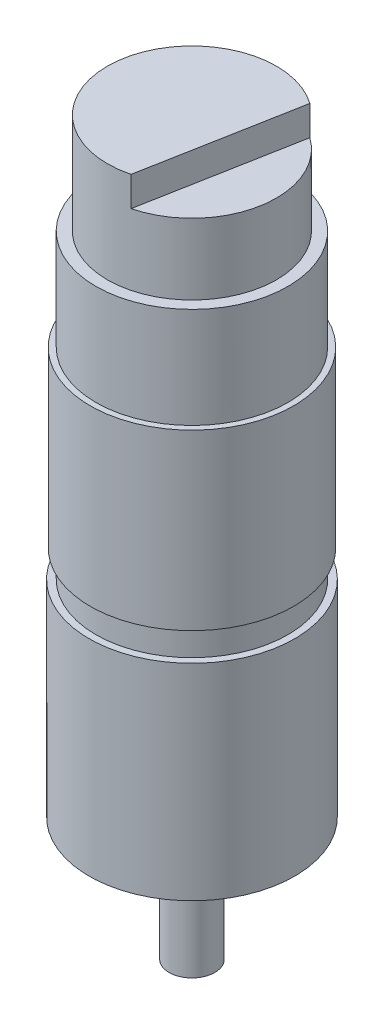
SolidWorks part; units mm, degrees
ref_plane "Front Plane" through (0, 0, 0) normal (0, 0, 1) x (1, 0, 0)
ref_plane "Top Plane" through (0, 0, 0) normal (0, 1, 0) x (1, 0, 0)
ref_plane "Right Plane" through (0, 0, 0) normal (1, 0, 0) x (0, 0, -1)
sketch "Sketch5" plane through (0, 0, 0) normal (0, 1, 0) x (1, 0, 0)
  circle A0 centre (0, 0) radius 22.5
extrude "Boss-Extrude4" add sketch "Sketch5" along normal blind 45
sketch "Sketch6" plane through (0, 45, 0) normal (0, 1, 0) x (-1, 0, 0)
  circle A0 centre (0, 0) radius 21
extrude "Boss-Extrude5" add sketch "Sketch6" along normal blind 6
sketch "Sketch7" plane through (0, 51, 0) normal (0, 1, 0) x (-1, 0, 0)
  circle A0 centre (0, 0) radius 22.25
extrude "Boss-Extrude6" add sketch "Sketch7" along normal blind 38
sketch "Sketch8" plane through (0, 89, 0) normal (0, 1, 0) x (-1, 0, 0)
  circle A0 centre (0, 0) radius 21
extrude "Boss-Extrude7" add sketch "Sketch8" along normal blind 22
sketch "Sketch9" plane through (0, 111, 0) normal (0, 1, 0) x (-1, 0, 0)
  circle A0 centre (0, 0) radius 18.5
extrude "Boss-Extrude9" add sketch "Sketch9" along normal blind 22
sketch "Sketch10" plane through (0, 133, 0) normal (0, 1, 0) x (-1, 0, 0)
  line L0 (-10.7161, -15.0803) -> (-4.5973, 17.9197)
  circle A0 centre (0, 0) radius 18.5 construction
  arc A1 (-4.5973, 17.9197) -> (-10.7161, -15.0803) centre (0, 0) ccw
extrude "Cut-Extrude1" cut sketch "Sketch10" against normal blind 6.5
sketch "Sketch16" plane through (0, 89, 0) normal (0, 1, 0) x (1, 0, 0)
  line L0 (0.6512, 20.9899) -> (0.69, 22.2393)
  line L1 (6.6895, 19.906) -> (7.0877, 21.0909)
  circle A0 centre (0, 0) radius 22.25 construction
  arc A1 (7.0877, 21.0909) -> (0.69, 22.2393) centre (0, 0) ccw
  arc A2 (6.6895, 19.906) -> (0.6512, 20.9899) centre (0, 0) ccw
  dimension "D1" = 6.5
extrude "Cut-Extrude3" cut sketch "Sketch16" against normal blind 38
sketch "Sketch17" plane through (0, 0, 0) normal (0, -1, 0) x (1, 0, 0)
  line L1 (-17.5646, -12) -> (17.5646, -12)
  line L2 (-17.5646, -12) -> (-17.5646, 12)
  line L3 (-17.5646, 12) -> (17.5646, 12)
  line L4 (17.5646, -12) -> (17.5646, 12)
  line L5 (-17.5646, -12) -> (17.5646, 12) construction
  line L6 (-17.5646, 12) -> (17.5646, -12) construction
  circle A0 centre (0, 0) radius 13
extrude "Boss-Extrude11" add sketch "Sketch17" along normal blind 2 contours L1 A0 L3
sketch "Sketch19" plane through (0, -2, 0) normal (0, -1, 0) x (1, 0, 0)
  circle A0 centre (0, 0) radius 5
extrude "Boss-Extrude12" add sketch "Sketch19" along normal blind 25
sketch "Sketch20" plane through (0, 0, 0) normal (0, -1, 0) x (1, 0, 0)
  line L1 (-12.578, -12.1673) -> (12.578, -12.1673)
  line L2 (-12.578, -12.1673) -> (-12.578, 12.1673)
  line L3 (-12.578, 12.1673) -> (12.578, 12.1673)
  line L4 (12.578, -12.1673) -> (12.578, 12.1673)
  line L5 (-12.578, -12.1673) -> (12.578, 12.1673) construction
  line L6 (-12.578, 12.1673) -> (12.578, -12.1673) construction
  circle A0 centre (0, 0) radius 17.5 construction
  circle A1 centre (-12.578, 12.1673) radius 2
  circle A2 centre (-12.578, -12.1673) radius 2
  circle A3 centre (12.578, -12.1673) radius 2
  circle A4 centre (12.578, 12.1673) radius 2
  dimension "D1" = 35
extrude "Cut-Extrude4" cut sketch "Sketch20" against normal blind 10 contours L3 A1 L2 | L2 A2 L1 | L1 A3 L4 | L4 A3 L1 | L4 A4 L3 | L3 A4 L4 | L2 A1 L3 | L1 A2 L2
